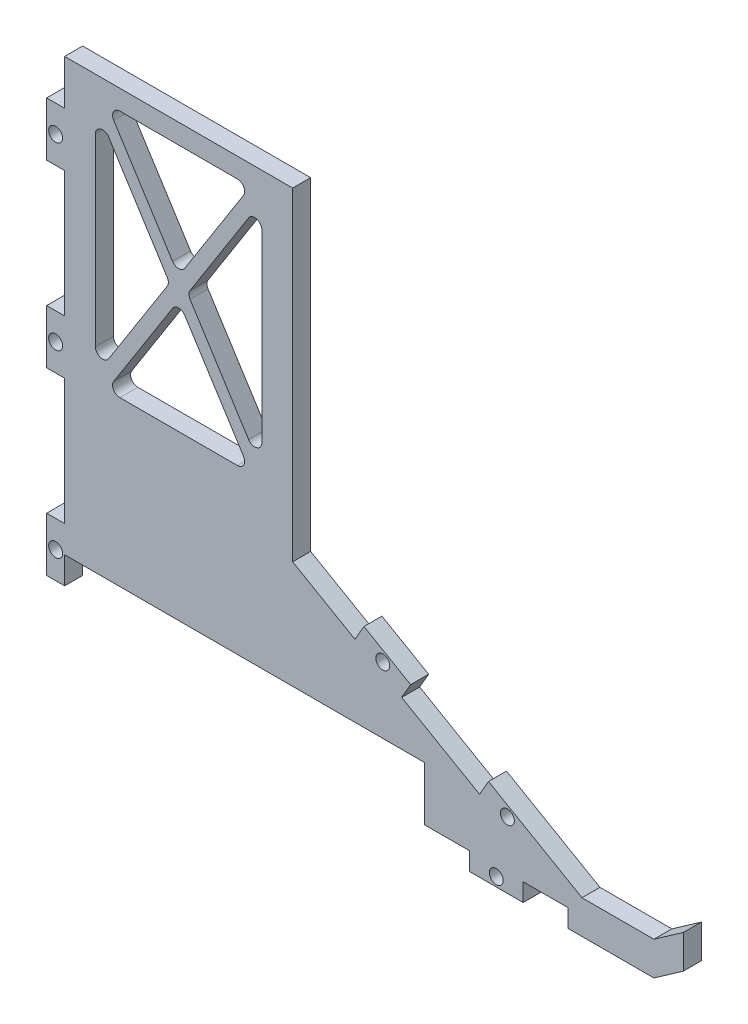
SolidWorks part; units mm, degrees
ref_plane "Front Plane" through (0, 0, 0) normal (0, 0, 1) x (1, 0, 0)
ref_plane "Top Plane" through (0, 0, 0) normal (0, 1, 0) x (1, 0, 0)
ref_plane "Right Plane" through (0, 0, 0) normal (1, 0, 0) x (0, 0, -1)
sketch "Sketch1" plane through (0, 0, 0) normal (0, 0, 1) x (1, 0, 0)
  line L0 (86.8648, 57.15) -> (185.8515, 0)
  line L1 (0, 0) -> (86.8648, 0)
  line L2 (0, 0) -> (0, 57.15)
  line L3 (0, 57.15) -> (86.8648, 57.15)
  line L5 (185.8515, 0) -> (86.8648, 0)
  dimension "D1" = 86.8648
  dimension "D2" = 30
  dimension "D3" = 114.3
extrude "Boss-Extrude1" add sketch "Sketch1" along normal blind 6.35
sketch "Sketch2" plane through (0, 0, 6.35) normal (0, 0, 1) x (1, 0, 0)
  line L0 (0, 0) -> (185.8515, 0) construction
  line L1 (6.35, 0) -> (133.35, 0)
  line L2 (6.35, 0) -> (6.35, 19.05)
  line L3 (6.35, 19.05) -> (133.35, 19.05)
  line L4 (133.35, 0) -> (133.35, 19.05)
  line L5 (0, 57.15) -> (0, 0) construction
  dimension "D1" = 127
  dimension "D2" = 19.05
  dimension "D3" = 6.35
extrude "Cut-Extrude1" cut sketch "Sketch2" against normal through all
sketch "Sketch3" plane through (0, 0, 6.35) normal (0, 0, 1) x (1, 0, 0)
  line L0 (86.8648, 57.15) -> (0, 57.15) construction
  line L1 (0, 57.15) -> (86.8648, 57.15)
  line L2 (0, 57.15) -> (0, 171.45)
  line L3 (0, 171.45) -> (86.8648, 171.45)
  line L4 (86.8648, 57.15) -> (86.8648, 171.45)
  line L5 (0, 57.15) -> (0, 0) construction
  dimension "D1" = 114.3
  dimension "D2" = 86.8648
extrude "Boss-Extrude2" add sketch "Sketch3" against normal blind 6.35
sketch "Sketch4" plane through (0, 0, 6.35) normal (0, 0, 1) x (1, 0, 0)
  line L0 (6.35, 19.05) -> (6.35, 0) construction
  line L1 (0, 0) -> (6.35, 0)
  line L2 (0, 0) -> (0, 9.525)
  line L3 (0, 9.525) -> (6.35, 9.525)
  line L4 (6.35, 0) -> (6.35, 9.525)
  line L5 (0, 171.45) -> (0, 0) construction
  line L6 (0, 28.575) -> (6.35, 28.575)
  line L7 (0, 28.575) -> (0, 73.025)
  line L8 (0, 73.025) -> (6.35, 73.025)
  line L9 (6.35, 28.575) -> (6.35, 73.025)
  line L11 (0, 92.075) -> (6.35, 92.075)
  line L12 (0, 92.075) -> (0, 136.525)
  line L13 (0, 136.525) -> (6.35, 136.525)
  line L14 (6.35, 92.075) -> (6.35, 136.525)
  line L15 (0, 171.45) -> (6.35, 171.45)
  line L16 (0, 171.45) -> (0, 155.575)
  line L17 (0, 155.575) -> (6.35, 155.575)
  line L18 (6.35, 171.45) -> (6.35, 155.575)
  dimension "D1" = 9.525
  dimension "D2" = 19.05
  dimension "D3" = 44.45
  dimension "D4" = 6.35
  dimension "D5" = 19.05
  dimension "D6" = 44.45
  dimension "D7" = 6.35
  dimension "D8" = 19.05
  dimension "D9" = 6.35
extrude "Cut-Extrude2" cut sketch "Sketch4" against normal through all
sketch "Sketch5" plane through (0, 0, 6.35) normal (0, 0, 1) x (1, 0, 0)
  line L0 (133.35, 0) -> (185.8515, 0) construction
  line L1 (149.225, 0) -> (168.275, 0)
  line L2 (149.225, 0) -> (149.225, -6.35)
  line L3 (149.225, -6.35) -> (168.275, -6.35)
  line L4 (168.275, 0) -> (168.275, -6.35)
  line L5 (6.35, 28.575) -> (6.35, 73.025) construction
  dimension "D1" = 19.05
  dimension "D2" = 6.35
  dimension "D3" = 142.875
extrude "Boss-Extrude3" add sketch "Sketch5" against normal blind 6.35
sketch "Sketch6" plane through (0, 0, 6.35) normal (0, 0, 1) x (1, 0, 0)
  line L0 (185.8515, 0) -> (86.8648, 57.15) construction
  line L1 (108.8618, 44.45) -> (125.3596, 34.925)
  line L2 (108.8618, 44.45) -> (112.0368, 49.9493)
  line L3 (112.0368, 49.9493) -> (128.5346, 40.4243)
  line L4 (125.3596, 34.925) -> (128.5346, 40.4243)
  dimension "D1" = 19.05
  dimension "D2" = 6.35
  dimension "D3" = 25.4
extrude "Boss-Extrude4" add sketch "Sketch6" against normal blind 6.35
pattern_linear "LPattern1" count 2 spacing 50.8 along (0.866, -0.5, 0) of "Boss-Extrude4"
sketch "Sketch8" [suppressed] plane through (0, 0, 6.35) normal (0, 0, 1) x (1, 0, 0)
  line L0 (0, 0) -> (185.8515, 0) construction
  line L1 (34.925, 0) -> (53.975, 0)
  line L2 (34.925, 0) -> (34.925, -6.35)
  line L3 (34.925, -6.35) -> (53.975, -6.35)
  line L4 (53.975, 0) -> (53.975, -6.35)
  dimension "D1" = 6.35
  dimension "D2" = 19.05
  dimension "D3" = 34.925
extrude "Boss-Extrude6" [suppressed] add sketch "Sketch8" against normal blind 6.35
pattern_linear "LPattern2" [suppressed] count 3 spacing 57.15
sketch "Sketch9" [suppressed] plane through (0, 0, 6.35) normal (0, 0, 1) x (1, 0, 0)
  line L0 (185.8515, 0) -> (86.8648, 57.15) construction
  line L1 (108.8618, 44.45) -> (125.3596, 34.925)
  line L2 (108.8618, 44.45) -> (112.0368, 49.9493)
  line L3 (112.0368, 49.9493) -> (128.5346, 40.4243)
  line L4 (125.3596, 34.925) -> (128.5346, 40.4243)
  dimension "D1" = 6.35
  dimension "D2" = 19.05
  dimension "D3" = 25.4
extrude "Boss-Extrude7" [suppressed] add sketch "Sketch9" against normal blind 6.35
pattern_linear "LPattern3" [suppressed] count 2 spacing 50.8
sketch "Sketch10" [suppressed] plane through (0, 0, 6.35) normal (0, 0, 1) x (1, 0, 0)
  line L1 (0, 57.15) -> (6.35, 57.15)
  line L2 (0, 57.15) -> (0, 28.575)
  line L3 (0, 28.575) -> (6.35, 28.575)
  line L4 (6.35, 57.15) -> (6.35, 28.575)
  line L5 (0, 0) -> (6.35, 0)
  line L6 (0, 0) -> (0, 9.525)
  line L7 (0, 9.525) -> (6.35, 9.525)
  line L8 (6.35, 0) -> (6.35, 9.525)
  dimension "D1" = 6.35
  dimension "D2" = 6.35
  dimension "D3" = 9.525
  dimension "D4" = 19.05
extrude "Cut-Extrude3" [suppressed] cut sketch "Sketch10" against normal through all
hole_wizard "#10 (0.1935) Diameter Hole1" positions "Sketch12" profile "Sketch11" hole size "#10" standard "ANSI Inch" end condition through all
sketch "Sketch12" plane through (0, 0, 6.35) normal (0, 0, 1) x (1, 0, 0)
  line L0 (3.175, 155.575) -> (3.175, 136.525) construction
  line L1 (0, 155.575) -> (6.35, 155.575) construction
  line L2 (6.35, 136.525) -> (0, 136.525) construction
  point P0 (3.175, 146.05)
  point P19 (3.175, 82.55)
  point P20 (3.175, 19.05)
  dimension "D1" = 3
sketch "Sketch11" plane through (3.175, 146.05, 6.35) normal (1, 0, 0) x (0, -1, 0)
  line L0 (0, 0) -> (0, 6.35)
  line L1 (0, 6.35) -> (2.4574, 6.35)
  line L2 (2.4574, 6.35) -> (2.4574, 0)
  line L5 (2.4574, 0) -> (0, 0)
  line L11 (0, -6.35) -> (0, 107.95) construction
  dimension "Thru Hole Dia." = 4.9149
  dimension "Thru Hole Depth" = 6.35
hole_wizard "#10 (0.1935) Diameter Hole2" positions "Sketch14" profile "Sketch13" hole size "#10" standard "ANSI Inch" end condition through all
sketch "Sketch14" plane through (0, 0, 6.35) normal (0, 0, 1) x (1, 0, 0)
  line L0 (110.4493, 47.1996) -> (126.9471, 37.6746) construction
  line L1 (112.0368, 49.9493) -> (108.8618, 44.45) construction
  line L2 (125.3596, 34.925) -> (128.5346, 40.4243) construction
  line L3 (149.225, -3.175) -> (168.275, -3.175) construction
  line L4 (149.225, 0) -> (149.225, -6.35) construction
  line L5 (168.275, -6.35) -> (168.275, 0) construction
  point P0 (118.6982, 42.4371)
  point P18 (162.6923, 17.0371)
  point P19 (158.75, -3.175)
  dimension "D1" = 2
sketch "Sketch13" plane through (118.6982, 42.4371, 6.35) normal (1, 0, 0) x (0, -1, 0)
  line L0 (0, 0) -> (0, 6.35)
  line L1 (0, 6.35) -> (2.4574, 6.35)
  line L2 (2.4574, 6.35) -> (2.4574, 0)
  line L5 (2.4574, 0) -> (0, 0)
  line L11 (0, -6.35) -> (0, 107.95) construction
  dimension "Thru Hole Dia." = 4.9149
  dimension "Thru Hole Depth" = 6.35
hole_wizard "#10 (0.1935) Diameter Hole4" [suppressed] positions "Sketch18" profile "Sketch17" hole size "#10" standard "ANSI Inch"
sketch "Sketch18" [suppressed] plane through (0, 0, 6.35) normal (0, 0, 1) x (1, 0, 0)
  line L0 (34.925, -3.175) -> (53.975, -3.175) construction
  line L1 (34.925, 0) -> (34.925, -6.35) construction
  line L2 (53.975, -6.35) -> (53.975, 0) construction
  line L3 (110.4493, 47.1996) -> (126.9471, 37.6746) construction
  line L4 (112.0368, 49.9493) -> (108.8618, 44.45) construction
  line L5 (125.3596, 34.925) -> (128.5346, 40.4243) construction
  line L6 (3.175, 28.575) -> (3.175, 9.525) construction
  line L7 (0, 28.575) -> (6.35, 28.575) construction
  line L8 (6.35, 9.525) -> (0, 9.525) construction
  point P0 (44.45, -3.175)
  point P19 (101.6, -3.175)
  point P20 (158.75, -3.175)
  point P21 (118.6982, 42.4371)
  point P39 (162.6923, 17.0371)
  point P40 (3.175, 19.05)
  dimension "D1" = 3
  dimension "D2" = 2
sketch "Sketch17" plane through (44.45, -3.175, 6.35) normal (1, 0, 0) x (0, -1, 0)
  line L0 (0, 0) -> (0, 6.35)
  line L1 (0, 6.35) -> (2.4574, 6.35)
  line L2 (2.4574, 6.35) -> (2.4574, 0)
  line L5 (2.4574, 0) -> (0, 0)
  line L11 (0, -6.35) -> (0, 107.95) construction
  dimension "Thru Hole Dia." = 4.9149
  dimension "Thru Hole Depth" = 6.35
sketch "Sketch20" plane through (0, 0, 6.35) normal (0, 0, 1) x (1, 0, 0)
  line L0 (172.5287, 15.0243) -> (189.0265, 5.4993)
  line L1 (189.0265, 5.4993) -> (214.4265, 5.4993)
  line L2 (214.4265, 5.4993) -> (224.8297, 12.7837)
  line L3 (224.8297, 12.7837) -> (224.8297, 0.9344)
  line L4 (185.8515, 0) -> (185.8515, -6.35) construction
  line L5 (168.275, -6.35) -> (214.4265, -6.35) construction
  line L6 (185.8515, 0) -> (169.3537, 9.525) construction
  line L7 (185.8515, 0) -> (169.3537, 9.525)
  line L8 (169.3537, 9.525) -> (172.5287, 15.0243)
  line L9 (185.8515, -6.35) -> (214.4265, -6.35)
  line L10 (214.4265, 5.4993) -> (214.4265, -6.35) construction
  line L11 (189.0265, 5.4993) -> (185.8515, 0) construction
  line L12 (214.4265, -6.35) -> (224.8297, 0.9344)
  line L13 (168.275, 0) -> (185.8515, 0) construction
  line L14 (184.15, 0) -> (185.8515, 0)
  line L15 (184.15, 0) -> (184.15, -6.35)
  line L16 (184.15, -6.35) -> (185.8515, -6.35)
  line L17 (185.8515, 0) -> (185.8515, -6.35) construction
  line L18 (168.275, -6.35) -> (168.275, 0) construction
  dimension "D1" = 15.875
  dimension "D2" = 12.7
  dimension "D3" = 145
  dimension "D4" = 25.4
extrude "Boss-Extrude8" add sketch "Sketch20" against normal blind 6.35
sketch "Sketch21" [suppressed] plane through (0, 0, 6.35) normal (0, 0, 1) x (1, 0, 0)
  line L0 (172.5287, 15.0243) -> (189.0265, 5.4993)
  line L1 (189.0265, 5.4993) -> (214.4265, 5.4993)
  line L2 (214.4265, 5.4993) -> (224.8297, 12.7837)
  line L3 (224.8297, 12.7837) -> (224.8297, 0.9344)
  line L4 (224.8297, 0.9344) -> (214.4265, -6.35)
  line L5 (214.4265, -6.35) -> (185.8515, -6.35)
  line L6 (185.8515, -6.35) -> (185.8515, 0) construction
  line L7 (185.8515, -6.35) -> (168.275, -6.35) construction
  line L8 (185.8515, 0) -> (169.3537, 9.525)
  line L9 (169.3537, 9.525) -> (172.5287, 15.0243)
  line L10 (214.4265, 5.4993) -> (214.4265, -6.35) construction
  line L11 (185.8515, 0) -> (189.0265, 5.4993) construction
  line L12 (168.275, 0) -> (185.8515, 0) construction
  line L13 (184.15, 0) -> (185.8515, 0)
  line L14 (184.15, 0) -> (184.15, -6.35)
  line L15 (184.15, -6.35) -> (185.8515, -6.35)
  line L17 (168.275, -6.35) -> (168.275, 0) construction
  dimension "D1" = 25.4
  dimension "D2" = 12.7
  dimension "D3" = 145
  dimension "D4" = 6.35
  dimension "D5" = 15.875
extrude "Boss-Extrude9" [suppressed] add sketch "Sketch21" against normal blind 6.35
sketch "Sketch22" plane through (0, 0, 6.35) normal (0, 0, 1) x (1, 0, 0)
  line L0 (17.2207, 161.925) -> (17.2207, 79.375)
  line L1 (17.2207, 79.375) -> (43.4324, 120.65)
  line L2 (43.4324, 120.65) -> (17.2207, 161.925)
  line L3 (17.2207, 120.65) -> (43.4324, 120.65) construction
  line L4 (75.9941, 79.375) -> (49.7824, 120.65)
  line L5 (49.7824, 120.65) -> (75.9941, 161.925)
  line L6 (75.9941, 161.925) -> (75.9941, 79.375)
  line L7 (43.4324, 120.65) -> (49.7824, 120.65) construction
  line L8 (21.2074, 164.4568) -> (46.6074, 124.46)
  line L9 (46.6074, 124.46) -> (72.0074, 164.4568)
  line L10 (72.0074, 164.4568) -> (21.2074, 164.4568)
  line L11 (17.2207, 161.925) -> (21.2074, 164.4568) construction
  line L12 (46.6074, 116.84) -> (72.0074, 76.8432)
  line L13 (72.0074, 76.8432) -> (21.2074, 76.8432)
  line L14 (21.2074, 76.8432) -> (46.6074, 116.84)
  line L15 (46.6074, 164.4568) -> (46.6074, 171.45) construction
  line L16 (86.8648, 171.45) -> (6.35, 171.45) construction
  line L17 (17.2207, 120.65) -> (6.35, 120.65) construction
  line L18 (6.35, 92.075) -> (6.35, 136.525) construction
  line L19 (46.6074, 116.84) -> (46.6074, 120.65) construction
  line L20 (46.6074, 120.65) -> (46.6074, 124.46) construction
  dimension "D1" = 50.8
  dimension "D2" = 3.81
  dimension "D3" = 6.35
  dimension "D4" = 82.55
  dimension "D5" = 50.8
extrude "Cut-Extrude4" cut sketch "Sketch22" against normal through all
fillet "Fillet1" radius 2.54 12 edges at (43.4324, 120.65, 3.175) (17.2207, 79.375, 3.175) (17.2207, 161.925, 3.175) (21.2074, 164.4568, 3.175) (72.0074, 164.4568, 3.175) (46.6074, 124.46, 3.175) (75.9941, 161.925, 3.175) (49.7824, 120.65, 3.175) (75.9941, 79.375, 3.175) (72.0074, 76.8432, 3.175) (21.2074, 76.8432, 3.175) (46.6074, 116.84, 3.175)
